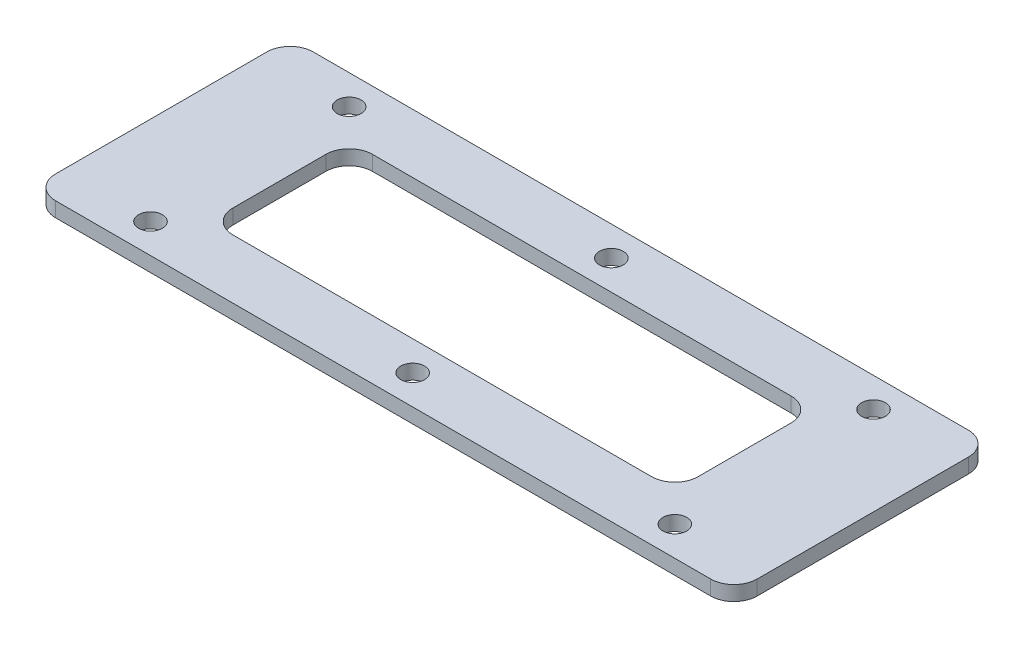
SolidWorks part; units mm, degrees
material "Silicon Rubber"
ref_plane "Front Plane" through (0, 0, 0) normal (0, 0, 1) x (1, 0, 0)
ref_plane "Top Plane" through (0, 0, 0) normal (0, 1, 0) x (1, 0, 0)
ref_plane "Right Plane" through (0, 0, 0) normal (1, 0, 0) x (0, 0, -1)
sketch "Sketch1" plane through (0, 0, 0) normal (0, 1, 0) x (1, 0, 0)
  line L0 (-75.4, 22.7) -> (-75.4, 0) construction
  line L4 (45, 15) -> (-45, 15)
  line L5 (50, -10) -> (50, 10)
  line L6 (-45, -15) -> (45, -15)
  line L7 (-50, 10) -> (-50, -10)
  line L8 (45, 15) -> (-45, 15)
  line L9 (50, -10) -> (50, 10)
  line L10 (-45, -15) -> (45, -15)
  line L11 (-50, 10) -> (-50, -10)
  line L16 (75.4, 0) -> (75.4, 22.7) construction
  line L17 (70.4, 27.7) -> (-70.4, 27.7) construction
  line L19 (-75.4, 0) -> (-75.4, -22.7) construction
  line L20 (-70.4, -27.7) -> (70.4, -27.7) construction
  line L21 (75.4, -22.7) -> (75.4, 0) construction
  line L28 (-75.4, 22.7) -> (-75.4, 0)
  line L36 (75.4, 0) -> (75.4, 22.7)
  line L37 (70.4, 27.7) -> (-70.4, 27.7)
  line L39 (-75.4, 0) -> (-75.4, -22.7)
  line L40 (-70.4, -27.7) -> (70.4, -27.7)
  line L41 (75.4, -22.7) -> (75.4, 0)
  arc A4 (50, 10) -> (45, 15) centre (45, 10) ccw
  arc A5 (45, -15) -> (50, -10) centre (45, -10) ccw
  arc A6 (-50, -10) -> (-45, -15) centre (-45, -10) ccw
  arc A7 (-45, 15) -> (-50, 10) centre (-45, 10) ccw
  arc A8 (50, 10) -> (45, 15) centre (45, 10) ccw
  arc A9 (45, -15) -> (50, -10) centre (45, -10) ccw
  arc A10 (-50, -10) -> (-45, -15) centre (-45, -10) ccw
  arc A11 (-45, 15) -> (-50, 10) centre (-45, 10) ccw
  arc A14 (75.4, 22.7) -> (70.4, 27.7) centre (70.4, 22.7) ccw construction
  arc A15 (-70.4, 27.7) -> (-75.4, 22.7) centre (-70.4, 22.7) ccw construction
  arc A16 (-75.4, -22.7) -> (-70.4, -27.7) centre (-70.4, -22.7) ccw construction
  arc A17 (70.4, -27.7) -> (75.4, -22.7) centre (70.4, -22.7) ccw construction
  arc A30 (75.4, 22.7) -> (70.4, 27.7) centre (70.4, 22.7) ccw
  arc A31 (-70.4, 27.7) -> (-75.4, 22.7) centre (-70.4, 22.7) ccw
  arc A32 (-75.4, -22.7) -> (-70.4, -27.7) centre (-70.4, -22.7) ccw
  arc A33 (70.4, -27.7) -> (75.4, -22.7) centre (70.4, -22.7) ccw
  circle A41 centre (-56.35, -21.35) radius 2.5527
  circle A42 centre (-56.35, -21.35) radius 2.5527
  circle A43 centre (0, -21.35) radius 2.5527
  circle A44 centre (0, -21.35) radius 2.5527
  circle A45 centre (56.35, -21.35) radius 2.5527
  circle A46 centre (56.35, -21.35) radius 2.5527
  circle A47 centre (56.35, 21.35) radius 2.5527
  circle A48 centre (56.35, 21.35) radius 2.5527
  circle A49 centre (0, 21.35) radius 2.5527
  circle A50 centre (0, 21.35) radius 2.5527
  circle A51 centre (-56.35, 21.35) radius 2.5527
  circle A52 centre (-56.35, 21.35) radius 2.5527
  dimension "D1" = 0
  dimension "D2" = 0
  dimension "D3" = 0
  dimension "D4" = 0
  dimension "D5" = 0
  dimension "D6" = 0
  dimension "D7" = 0
extrude "Boss-Extrude1" add sketch "Sketch1" along normal blind 3.175
